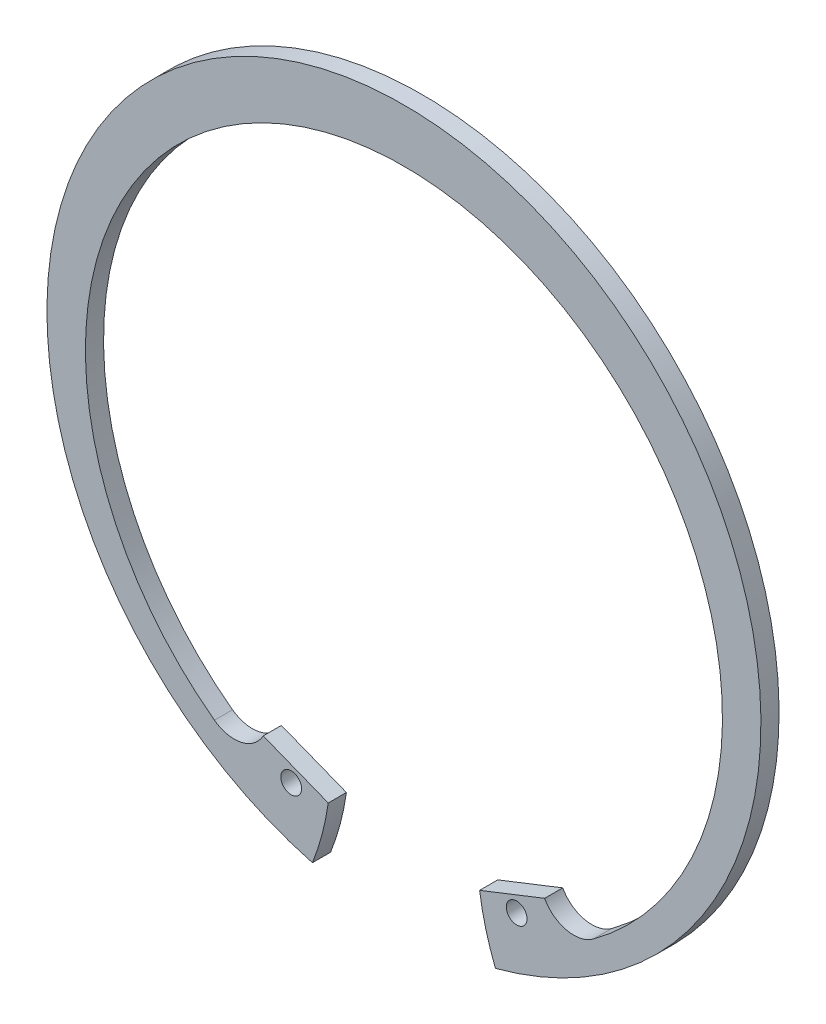
SolidWorks part; units mm, degrees
material "AISI 304"
ref_plane "Front Plane" through (0, 0, 0) normal (0, 0, 1) x (1, 0, 0)
ref_plane "Top Plane" through (0, 0, 0) normal (0, 1, 0) x (1, 0, 0)
ref_plane "Right Plane" through (0, 0, 0) normal (1, 0, 0) x (0, 0, -1)
sketch "Sketch1" plane through (0, 0, 0) normal (0, 0, 1) x (1, 0, 0)
  line L0 (0, 54.4957) -> (0, 46.3931) construction
  line L1 (-31.2574, -44.6403) -> (-28.9264, -41.3112) construction
  line L2 (0, 0) -> (0, -54.4957) construction
  line L3 (-11.3157, -43.655) -> (-13.6738, -52.7523) construction
  line L4 (-11.3157, -43.655) -> (-14.4907, -43.655) construction
  circle A0 centre (0, 0) radius 52.1589 construction
  circle A1 centre (0, 0) radius 54.4957 construction
  circle A2 centre (0, 0) radius 49.2125 construction
  dimension "Ring OD" = 108.9914
  dimension "For ID" = 98.425
  dimension "Maximum Section" = 8.1026
  dimension "D1" = 145
  dimension "Minimum Section" = 4.064
  dimension "Gap Width" = 22.6314
  dimension "Lug Height" = 9.398
  dimension "Hole Diameter" = 3.175
sketch "Sketch2" plane through (0, 0, 0) normal (1, 0, 0) x (0, 0, -1)
  line L0 (-1.524, 54.4957) -> (1.524, 54.4957) construction
  line L1 (-1.3843, -54.4957) -> (1.3843, -54.4957) construction
  point P3 (0, 54.4957)
  point P7 (0, -54.4957)
  point P8 (-1.3843, -54.4957)
  point P10 (1.3843, -54.4957)
  point P11 (-1.524, 54.4957)
  point P12 (1.524, 54.4957)
  dimension "For Groove Width" = 3.048
  dimension "Ring Thickness" = 2.7686
sketch "Sketch3" plane through (0, 0, 0) normal (0, 0, 1) x (1, 0, 0)
  line L0 (-13.6738, -52.7523) -> (-11.3157, -43.655)
  line L1 (-11.3157, -43.655) -> (-21.4761, -39.6558)
  line L2 (0, 0) -> (-16.3959, -41.6554) construction
  line L3 (-28.9264, -41.3112) -> (28.9264, -41.3112) construction
  line L4 (0, 0) -> (0, -54.4957) construction
  line L5 (-21.4761, -39.6558) -> (0, 0) construction
  line L6 (-16.3959, -41.6554) -> (-17.2102, -43.7241) construction
  line L7 (-17.2102, -43.7241) -> (-18.0244, -45.7929) construction
  line L8 (0, 54.4957) -> (0, 46.3931) construction
  line L9 (11.3157, -43.655) -> (21.4761, -39.6558)
  line L10 (13.6738, -52.7523) -> (11.3157, -43.655)
  arc A0 (-13.6738, -52.7523) -> (13.6738, -52.7523) centre (0, 0) cw
  circle A1 centre (0, 0) radius 54.4957 construction
  arc A2 (-28.9264, -41.3112) -> (28.9264, -41.3112) centre (0, -2.2293) cw
  arc A3 (-28.9264, -41.3112) -> (-21.4761, -39.6558) centre (-25.9199, -37.2492) ccw
  circle A4 centre (-17.2102, -43.7241) radius 1.5875
  circle A5 centre (0, 0) radius 50.4317 construction
  arc A6 (28.9264, -41.3112) -> (21.4761, -39.6558) centre (25.9199, -37.2492) cw
  circle A7 centre (17.2102, -43.7241) radius 1.5875
  circle A8 centre (0, 0) radius 49.2125 construction
  point P3 (0, -41.3112)
  dimension "D1" = 3.175
extrude "Boss-Extrude1" add sketch "Sketch3" against normal up to vertex (1.3843 mm away) and the other way up to vertex (1.3843 mm away) up to point (0, -54.4957, -1.3843) other way up to point (0, -54.4957, 1.3843)
sketch "Sketch4" plane through (0, 0, 0) normal (0, 0, 1) x (1, 0, 0)
  line L0 (-11.3157, -43.655) -> (-21.4761, -39.6558) construction
  line L1 (-11.3157, -43.655) -> (-13.6738, -52.7523) construction
  line L2 (-13.9687, -52.675) -> (-11.5521, -43.562) construction
  line L3 (-11.5521, -43.562) -> (0, 0) construction
  line L4 (-13.9687, -52.675) -> (-13.9687, -66.6437)
  line L5 (-13.9687, -66.6437) -> (0, -66.6437)
  line L6 (0, -66.6437) -> (0, -54.4957)
  line L7 (0, -54.4957) -> (0, -43.562)
  line L8 (0, 0) -> (0, -54.4957) construction
  line L9 (0, -43.562) -> (-11.5521, -43.562)
  arc A0 (-11.5521, -43.562) -> (-13.9687, -52.675) centre (-51.2749, -37.9049) cw
  circle A1 centre (0, 0) radius 54.4957 construction
  dimension "D1" = 0.254
extrude "Cut-Extrude1" cut sketch "Sketch4" against normal through all both and the other way through all
mirror "Mirror1" about plane through (0, 0, 0) normal (1, 0, 0) of "Cut-Extrude1"
equation "\"D1@Sketch3\"=\"Hole Diameter@Sketch1\""
